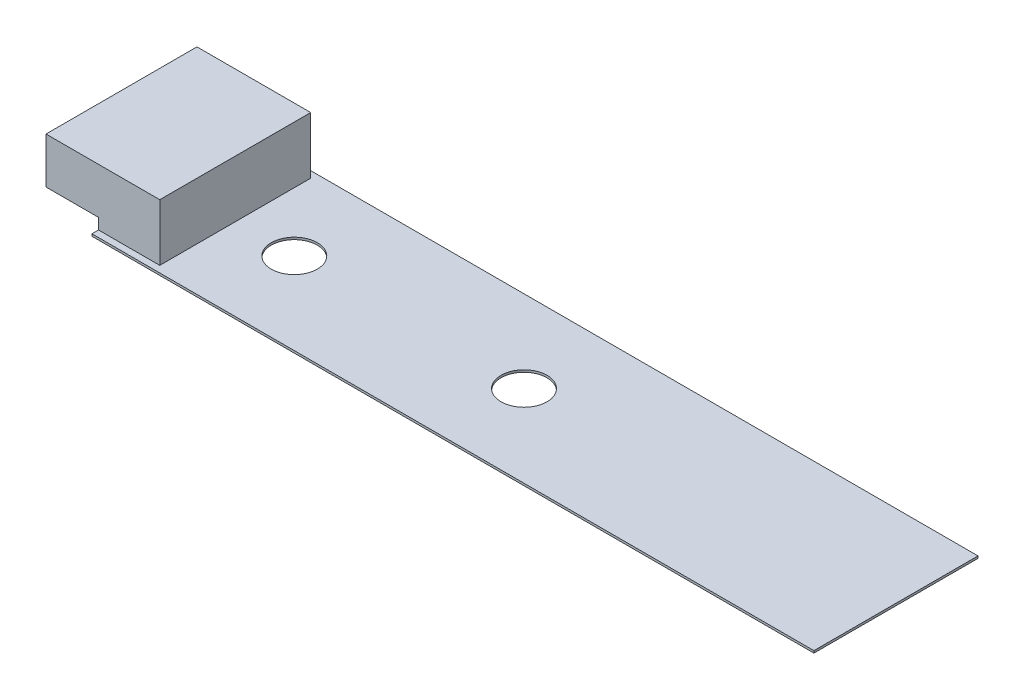
SolidWorks part; units mm, degrees
ref_plane "Front Plane" through (0, 0, 0) normal (0, 0, 1) x (1, 0, 0)
ref_plane "Top Plane" through (0, 0, 0) normal (0, 1, 0) x (1, 0, 0)
ref_plane "Right Plane" through (0, 0, 0) normal (1, 0, 0) x (0, 0, -1)
sketch "Sketch1" plane through (0, 0, 0) normal (0, 1, 0) x (1, 0, 0)
  line L1 (0, 0) -> (33, 0)
  line L2 (0, 0) -> (0, 7.5)
  line L3 (0, 7.5) -> (33, 7.5)
  line L4 (33, 0) -> (33, 7.5)
  dimension "D1" = 7.5
  dimension "D2" = 33
extrude "Boss-Extrude1" add sketch "Sketch1" along normal blind 0.1
sketch "Sketch2" plane through (0, 0.1, 0) normal (0, 1, 0) x (1, 0, 0)
  line L0 (0, 0) -> (33, 0) construction
  line L1 (-2.4, 7.2) -> (2.8, 7.2)
  line L2 (-2.4, 7.2) -> (-2.4, 0.3)
  line L3 (-2.4, 0.3) -> (2.8, 0.3)
  line L4 (2.8, 7.2) -> (2.8, 0.3)
  line L5 (33, 7.5) -> (0, 7.5) construction
  line L6 (0, 7.5) -> (0, 0) construction
  dimension "D1" = 0.3
  dimension "D2" = 5.2
  dimension "D3" = 0.3
  dimension "D4" = 2.4
extrude "Boss-Extrude2" add sketch "Sketch2" along normal blind 2.6
chamfer "Chamfer1" distance 0.5 angle 45 2 edges at (-1.2, 0.1, -0.3) (-1.2, 0.1, -7.2)
sketch "Sketch3" plane through (0, 0, 0) normal (0, -1, 0) x (1, 0, 0)
  line L0 (-1000, -3.75) -> (49000, -3.75) construction
  line L1 (0, -6.7) -> (0, -0.8) construction
  circle A0 centre (5.5, -3.75) radius 1.05
  circle A1 centre (16, -3.75) radius 1.05
  point P5 (0, -3.75)
  dimension "D1" = 2.1
  dimension "D2" = 2.1
  dimension "D3" = 5.5
  dimension "D4" = 16
extrude "Cut-Extrude1" cut sketch "Sketch3" against normal blind 2.6
